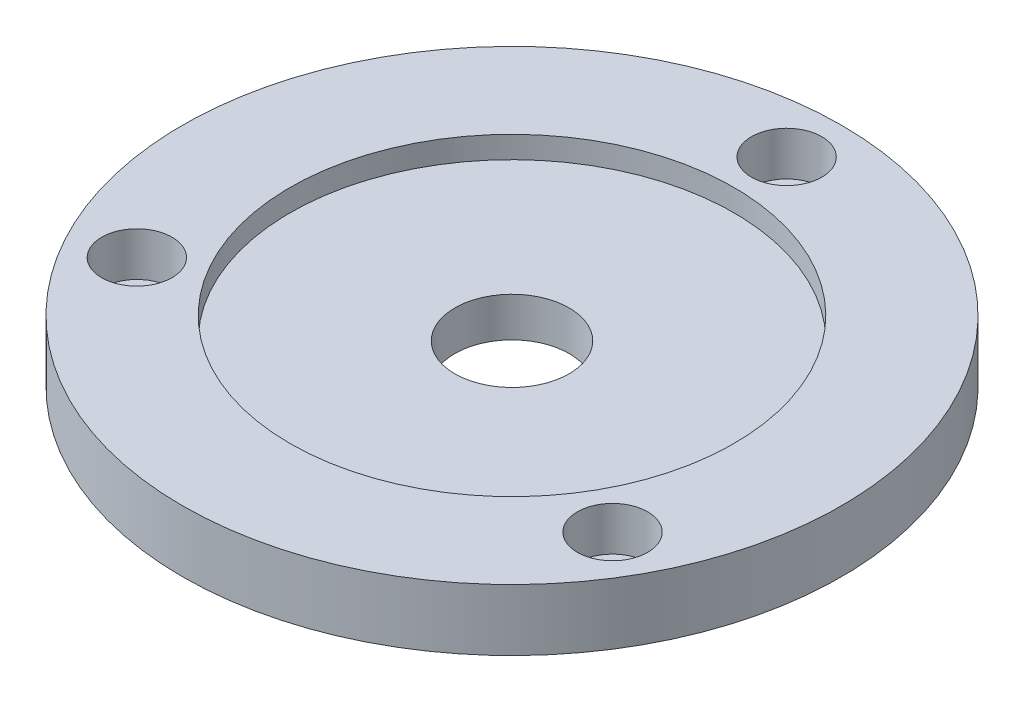
SolidWorks part; units mm, degrees
ref_plane "Front Plane" through (0, 0, 0) normal (0, 0, 1) x (1, 0, 0)
ref_plane "Top Plane" through (0, 0, 0) normal (0, 1, 0) x (1, 0, 0)
ref_plane "Right Plane" through (0, 0, 0) normal (1, 0, 0) x (0, 0, -1)
sketch "Sketch1" plane through (0, 0, 0) normal (0, 1, 0) x (1, 0, 0)
  circle A0 centre (0, 0) radius 75
  dimension "D1" = 150
extrude "Boss-Extrude1" add sketch "Sketch1" along normal blind 14
sketch "Sketch2" plane through (0, 14, 0) normal (0, 1, 0) x (1, 0, 0)
  circle A0 centre (0, 0) radius 13
  dimension "D1" = 26
sketch "Sketch4" plane through (0, 14, 0) normal (0, 1, 0) x (1, 0, 0)
  line L0 (0, 0) -> (0, 62.5) construction
  line L1 (0, 0) -> (54.1266, -31.25) construction
  line L2 (0, 0) -> (-54.1266, -31.25) construction
  circle A0 centre (0, 62.5) radius 5
  circle A1 centre (-54.1266, -31.25) radius 5
  circle A2 centre (54.1266, -31.25) radius 5
  circle A3 centre (0, 0) radius 62.5
  dimension "D1" = 10
  dimension "D2" = 10
  dimension "D3" = 10
  dimension "D4" = 62.5
  dimension "D5" = 120
extrude "Cut-Extrude4" cut sketch "Sketch4" against normal through all contours A3 A0 | A0 A3 | A2 A3 | A3 A2 | A3 A1 | A1 A3
extrude "Cut-Extrude5" cut sketch "Sketch2" against normal through all
sketch "Sketch5" plane through (0, 14, 0) normal (0, 1, 0) x (-1, 0, 0)
  circle A0 centre (0, 0) radius 50.5
  dimension "D1" = 101
extrude "Cut-Extrude6" cut sketch "Sketch5" against normal blind 5
sketch "Sketch6" plane through (0, 14, 0) normal (0, 1, 0) x (1, 0, 0)
  circle A0 centre (-54.1266, -31.25) radius 8
  circle A1 centre (0, 62.5) radius 8
  circle A2 centre (54.1266, -31.25) radius 8
  dimension "D1" = 16
  dimension "D2" = 16
  dimension "D3" = 16
extrude "Cut-Extrude7" cut sketch "Sketch6" against normal blind 10
